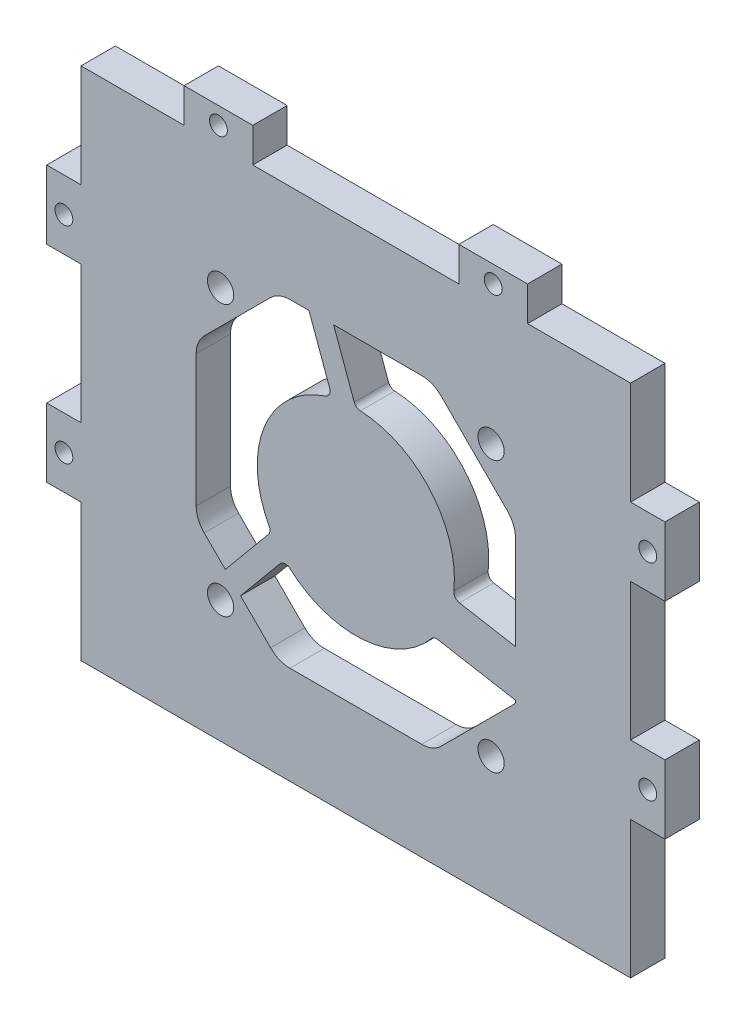
SolidWorks part; units mm, degrees
ref_plane "Front Plane" through (0, 0, 0) normal (0, 0, 1) x (1, 0, 0)
ref_plane "Top Plane" through (0, 0, 0) normal (0, 1, 0) x (1, 0, 0)
ref_plane "Right Plane" through (0, 0, 0) normal (1, 0, 0) x (0, 0, -1)
sketch "Sketch1" plane through (0, 0, 0) normal (0, 0, 1) x (1, 0, 0)
  line L0 (-50.8, 39.9954) -> (-50.8, 20.9454) construction
  line L1 (50.8, 39.9954) -> (-50.8, 39.9954)
  line L2 (50.8, 39.9954) -> (50.8, -55.2546)
  line L3 (50.8, -55.2546) -> (-50.8, -55.2546)
  line L4 (-50.8, 39.9954) -> (-50.8, -55.2546)
  line L5 (0, 0) -> (0, -55.2546) construction
  line L7 (-31.75, 39.9954) -> (-57.15, 39.9954) construction
  line L10 (-50.8, -55.2546) -> (-57.15, -55.2546) construction
  point P0 (0, 0)
extrude "Boss-Extrude1" add sketch "Sketch1" along normal blind 6.35
sketch "Sketch2" plane through (0, 0, 6.35) normal (0, 0, 1) x (1, 0, 0)
  line L0 (50.8, 39.9954) -> (-50.8, 39.9954) construction
  line L1 (-31.75, 39.9954) -> (-19.05, 39.9954)
  line L2 (-31.75, 39.9954) -> (-31.75, 46.3454)
  line L3 (-31.75, 46.3454) -> (-19.05, 46.3454)
  line L4 (-19.05, 39.9954) -> (-19.05, 46.3454)
  line L5 (-19.05, 43.1704) -> (19.05, 43.1704) construction
  line L6 (19.05, 39.9954) -> (31.75, 39.9954)
  line L7 (19.05, 39.9954) -> (19.05, 46.3454)
  line L8 (19.05, 46.3454) -> (31.75, 46.3454)
  line L9 (31.75, 39.9954) -> (31.75, 46.3454)
  line L10 (0, 43.1704) -> (0, 0) construction
  line L11 (-31.75, 46.3454) -> (-19.05, 39.9954) construction
  line L12 (19.05, 46.3454) -> (31.75, 39.9954) construction
  line L13 (-19.05, 46.3454) -> (-19.05, 39.9954) construction
  line L14 (50.8, -55.2546) -> (50.8, 39.9954) construction
  line L15 (50.8, 20.9454) -> (57.15, 20.9454)
  line L16 (50.8, 20.9454) -> (50.8, 8.2454)
  line L17 (50.8, 8.2454) -> (57.15, 8.2454)
  line L18 (57.15, 20.9454) -> (57.15, 8.2454)
  line L19 (-50.8, 39.9954) -> (-50.8, -55.2546) construction
  line L20 (-50.8, 20.9454) -> (-57.15, 20.9454)
  line L21 (-50.8, 20.9454) -> (-50.8, 8.2454)
  line L22 (-50.8, 8.2454) -> (-57.15, 8.2454)
  line L23 (-57.15, 20.9454) -> (-57.15, 8.2454)
  line L24 (-57.15, 20.9454) -> (-50.8, 8.2454) construction
  line L25 (50.8, 20.9454) -> (57.15, 8.2454) construction
  line L26 (-57.15, 20.9454) -> (-50.8, 20.9454) construction
  line L27 (-57.15, -17.1546) -> (-50.8, -29.8546) construction
  line L28 (-50.8, -17.1546) -> (-57.15, -17.1546)
  line L29 (-50.8, -17.1546) -> (-50.8, -29.8546)
  line L30 (-50.8, -29.8546) -> (-57.15, -29.8546)
  line L31 (-57.15, -17.1546) -> (-57.15, -29.8546)
  line L32 (50.8, -17.1546) -> (57.15, -17.1546)
  line L33 (50.8, -17.1546) -> (50.8, -29.8546)
  line L34 (50.8, -29.8546) -> (57.15, -29.8546)
  line L35 (57.15, -17.1546) -> (57.15, -29.8546)
  line L36 (50.8, -17.1546) -> (57.15, -29.8546) construction
  line L37 (50.8, 8.2454) -> (50.8, -17.1546) construction
  line L38 (57.15, 8.2454) -> (57.15, -17.1546) construction
  line L39 (50.8, -17.1546) -> (57.15, -17.1546) construction
  circle A0 centre (-25.4, 43.1704) radius 1.651
  circle A1 centre (25.4, 43.1704) radius 1.651
  circle A2 centre (-53.975, 14.5954) radius 1.651
  circle A3 centre (53.975, 14.5954) radius 1.651
  circle A4 centre (-53.975, -23.5046) radius 1.651
  circle A5 centre (53.975, -23.5046) radius 1.651
  dimension "D3" = 3.302
  dimension "D1" = 12.7
  dimension "D2" = 6.35
extrude "Boss-Extrude2" add sketch "Sketch2" against normal up to surface (6.35 mm away) up to face at (0, -7.6296, 0)
sketch "Sketch3" plane through (0, 0, 6.35) normal (0, 0, 1) x (1, 0, 0)
  line L0 (-19.05, 46.3454) -> (19.05, 46.3454) construction
  line L2 (0, 46.3454) -> (0, 14.5954) construction
  circle A0 centre (0, 14.5954) radius 6.35
  dimension "D1" = 12.7
  dimension "D2" = 31.75
ref_plane "Plane1" through (0, -7.6296, 0) normal (0, 1, 0) x (1, 0, 0)
sketch "Sketch7" plane through (0, 0, 6.35) normal (0, 0, 1) x (1, 0, 0)
  line L0 (0.6875, -10.0891) -> (75.2799, -10.0891) construction
sketch "Sketch5" plane through (0, 0, 6.35) normal (0, 0, 1) x (1, 0, 0)
  line L0 (-24.1285, -27.3052) -> (-15.6066, -17.0406)
  line L1 (-21.3173, -30.1165) -> (-13.136, -20.262)
  line L2 (29.5167, -12.8342) -> (17.9476, -10.7942)
  line L3 (-29.5167, 6.6579) -> (-29.5167, -21.9171)
  line L4 (14.4301, -18.7609) -> (29.5167, -21.4211)
  line L5 (29.5167, -21.4211) -> (29.5167, -21.9171)
  line L6 (-4.11, 21.8871) -> (14.2875, 21.8871)
  line L7 (-14.2875, 21.8871) -> (-8.6644, 21.8871)
  line L8 (-21.3173, -30.1165) -> (-14.2875, -37.1463)
  line L11 (29.5167, 6.6579) -> (29.5167, -12.8342)
  line L13 (-14.2875, -37.1463) -> (14.2875, -37.1463)
  line L15 (-29.5167, 6.6579) -> (-14.2875, 21.8871)
  line L17 (14.2875, 21.8871) -> (29.5167, 6.6579)
  line L18 (-29.5167, -21.9171) -> (-24.1285, -27.3052)
  line L19 (14.2875, -37.1463) -> (29.5167, -21.9171)
  line L20 (-21.9021, -29.5317) -> (21.9021, 14.2725) construction
  line L21 (-25, -32.6296) -> (-21.9021, -29.5317) construction
  line L22 (21.9021, 14.2725) -> (25, 17.3704) construction
  line L23 (-29.5167, 9.8005) -> (-19.8423, 19.4748) construction
  line L24 (-8.6644, 21.8871) -> (-4.3616, 10.0653)
  line L25 (-4.11, 21.8871) -> (0, 10.5949)
  arc A0 (-13.136, -20.262) -> (14.4301, -18.7609) centre (0, -7.6296) ccw
  arc A1 (17.9476, -10.7942) -> (0, 10.5949) centre (0, -7.6296) ccw
  circle A2 centre (-25, 17.3704) radius 2.4257
  circle A3 centre (25, 17.3704) radius 2.4257
  circle A4 centre (25, -32.6296) radius 2.4257
  circle A5 centre (-25, -32.6296) radius 2.4257
  arc A11 (-4.3616, 10.0653) -> (-15.6066, -17.0406) centre (0, -7.6296) ccw
  circle A26 centre (-25, -32.6296) radius 2.159 construction
  circle A28 centre (-25, -32.6296) radius 2.159 construction
  circle A30 centre (25, -32.6296) radius 2.159 construction
  circle A32 centre (25, -32.6296) radius 2.159 construction
  circle A33 centre (-25, 17.3704) radius 2.159 construction
  circle A34 centre (-25, 17.3704) radius 2.159 construction
  circle A35 centre (25, 17.3704) radius 2.159 construction
  circle A36 centre (25, 17.3704) radius 2.159 construction
  point P12 (0, -7.6296)
  dimension "D1" = 36.449
  dimension "D11" = 4.8514
  dimension "D2" = 28.575
  dimension "D3" = 4.4442
  dimension "D4" = 70
  dimension "D5" = 80
  dimension "D6" = 84.7
  dimension "D7" = 3.9587
  dimension "D8" = 4.2797
  dimension "D9" = 8.4564
  dimension "D10" = 7.62
extrude "Cut-Extrude1" cut sketch "Sketch5" against normal through all
fillet "Fillet1" radius 5.08 7 edges at (14.2875, -37.1463, 3.175) (-14.2875, -37.1463, 3.175) (-29.5167, -21.9171, 3.175) (29.5167, 6.6579, 3.175) (14.2875, 21.8871, 3.175) (-14.2875, 21.8871, 3.175) (-29.5167, 6.6579, 3.175)
fillet "Fillet2" radius 1.27 6 edges at (-15.6066, -17.0406, 3.175) (-13.136, -20.262, 3.175) (14.4301, -18.7609, 3.175) (17.9476, -10.7942, 3.175) (0, 10.5949, 3.175) (-4.3616, 10.0653, 3.175)
